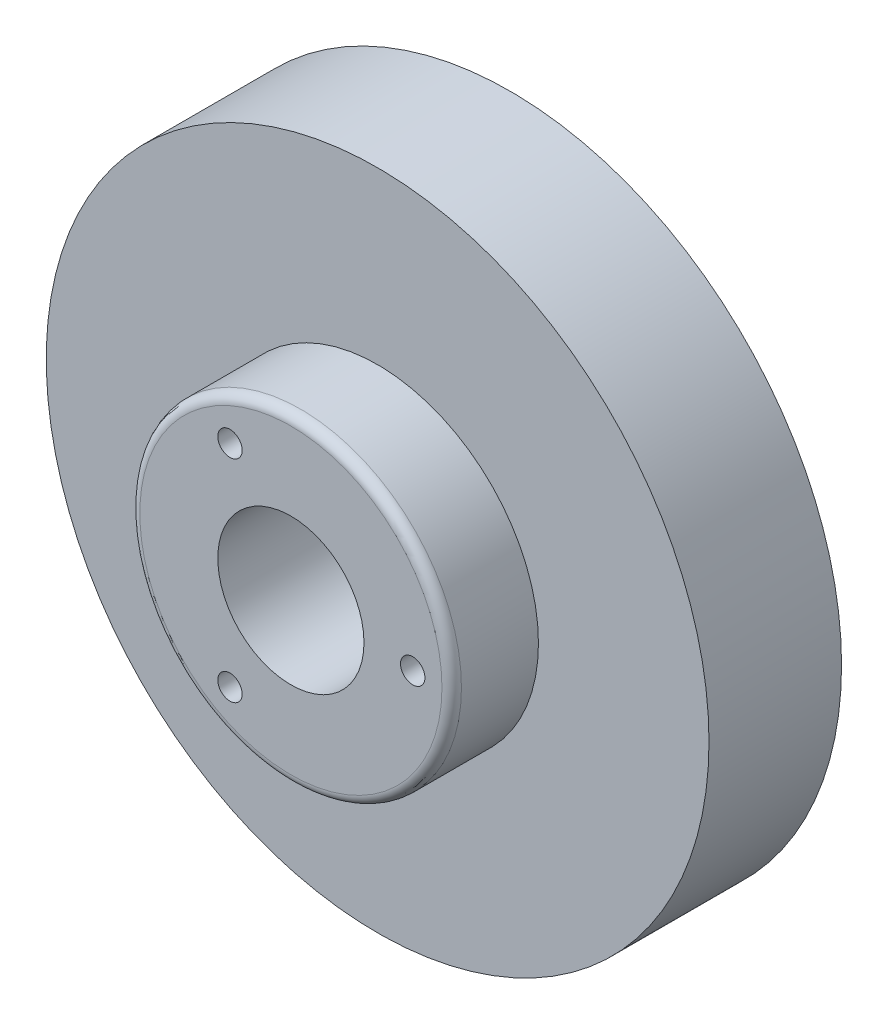
SolidWorks part; units mm, degrees
ref_plane "Спереди" through (0, 0, 0) normal (0, 0, 1) x (1, 0, 0)
ref_plane "Сверху" through (0, 0, 0) normal (0, 1, 0) x (1, 0, 0)
ref_plane "Справа" through (0, 0, 0) normal (1, 0, 0) x (0, 0, -1)
sketch "Эскиз1" plane through (0, 0, 0) normal (0, 0, 1) x (1, 0, 0)
  circle A0 centre (0, 0) radius 34
  dimension "D1" = 68
extrude "Бобышка-Вытянуть1" add sketch "Эскиз1" along normal blind 13.6
sketch "Эскиз2" plane through (0, 0, 13.6) normal (0, 0, 1) x (1, 0, 0)
  circle A0 centre (0, 0) radius 16.5
  dimension "D1" = 33
extrude "Бобышка-Вытянуть2" add sketch "Эскиз2" along normal blind 8.9
fillet "Скругление1" radius 1 1 edges at (16.5, 0, 22.5)
sketch "Эскиз3" plane through (0, 0, 0) normal (0, 0, -1) x (-1, 0, 0)
  circle A0 centre (0, 0) radius 4
  dimension "D1" = 8
extrude "Вырез-Вытянуть1" cut sketch "Эскиз3" against normal through all
sketch "Эскиз4" plane through (0, 0, 22.5) normal (0, 0, 1) x (1, 0, 0)
  circle A0 centre (0, 0) radius 7.5
  dimension "D1" = 15
extrude "Вырез-Вытянуть2" cut sketch "Эскиз4" against normal through all
sketch "Эскиз5" [suppressed] plane through (0, 0, 22.5) normal (0, 0, 1) x (1, 0, 0)
  line L0 (0, 15.5) -> (0, -15.5) construction
  line L1 (15.5, 0) -> (-15.5, 0) construction
  circle A0 centre (0, 0) radius 15.5 construction
  circle A1 centre (0, 0) radius 12.5 construction
  dimension "D1" = 25
hole_wizard "Отверстие обработанное метчиком M3x0.51" [suppressed] positions "Эскиз7" profile "Эскиз6" tap size "M3x0.5" standard "Ansi Metric"
sketch "Эскиз7" [suppressed] plane through (0, 0, 22.5) normal (0, 0, 1) x (1, 0, 0)
  line L0 (0, 15.5) -> (0, -15.5) construction
  line L1 (15.5, 0) -> (-15.5, 0) construction
  circle A0 centre (0, 0) radius 12.5 construction
  point P0 (0, 12.5)
  point P6 (12.5, 0)
  point P10 (0, -12.5)
  point P12 (-12.5, 0)
sketch "Эскиз6" plane through (0, 12.5, 22.5) normal (1, 0, 0) x (0, -1, 0)
  line L0 (0, 0) -> (0, 22.5)
  line L1 (0, 22.5) -> (1.25, 22.5)
  line L2 (1.25, 22.5) -> (1.25, 0)
  line L5 (1.25, 0) -> (0, 0)
  line L11 (0, -6.35) -> (0, 107.95) construction
  dimension "Диаметр проходного сверла" = 2.5
  dimension "Глубина проходного сверла" = 22.5
cosmetic thread "Отверстие резьбы1" [suppressed] parameters "D2"=3
cosmetic thread "Отверстие резьбы2" [suppressed] parameters "D2"=3
cosmetic thread "Отверстие резьбы3" [suppressed] parameters "D2"=3
cosmetic thread "Отверстие резьбы4" [suppressed] parameters "D2"=3
sketch "Эскиз8" plane through (0, 0, 22.5) normal (0, 0, 1) x (1, 0, 0)
  line L0 (-15.5, 0) -> (15.5, 0) construction
  line L1 (-7.75, 13.4234) -> (7.75, -13.4234) construction
  line L2 (7.75, 13.4234) -> (-7.75, -13.4234) construction
  circle A0 centre (0, 0) radius 15.5 construction
  circle A1 centre (0, 0) radius 12.5 construction
  dimension "D3" = 25
  dimension "D1" = 60
  dimension "D2" = 60
hole_wizard "Отверстие обработанное метчиком M3x0.52" positions "Эскиз10" profile "Эскиз9" tap size "M3x0.5" standard "Ansi Metric" end condition through all
sketch "Эскиз10" plane through (0, 0, 22.5) normal (0, 0, 1) x (1, 0, 0)
  line L0 (-7.75, 13.4234) -> (7.75, -13.4234) construction
  line L1 (7.75, 13.4234) -> (-7.75, -13.4234) construction
  line L2 (-15.5, 0) -> (15.5, 0) construction
  circle A0 centre (0, 0) radius 12.5 construction
  point P0 (-6.25, 10.8253)
  point P6 (-6.25, -10.8253)
  point P10 (12.5, 0)
sketch "Эскиз9" plane through (-6.25, 10.8253, 22.5) normal (1, 0, 0) x (0, -1, 0)
  line L0 (0, 0) -> (0, 22.5)
  line L1 (0, 22.5) -> (1.25, 22.5)
  line L2 (1.25, 22.5) -> (1.25, 0)
  line L5 (1.25, 0) -> (0, 0)
  line L11 (0, -6.35) -> (0, 107.95) construction
  dimension "Диаметр проходного сверла" = 2.5
  dimension "Глубина проходного сверла" = 22.5
cosmetic thread "Отверстие резьбы5" parameters "D2"=3
cosmetic thread "Отверстие резьбы6" parameters "D2"=3
cosmetic thread "Отверстие резьбы7" parameters "D2"=3
